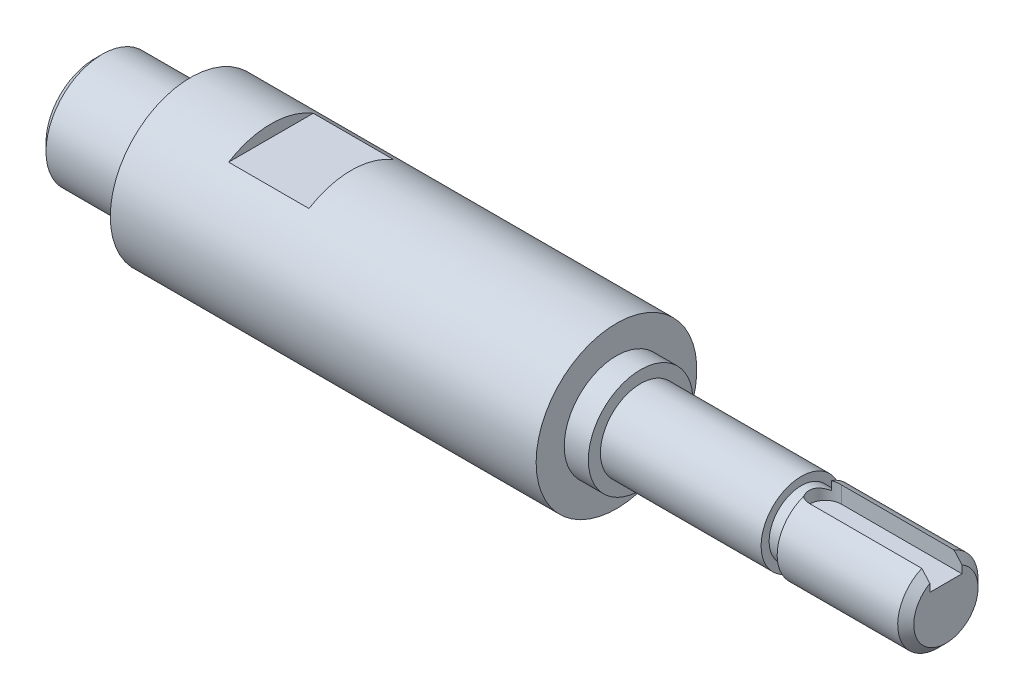
SolidWorks part; units mm, degrees
ref_plane "前视基准面" through (0, 0, 0) normal (0, 0, 1) x (1, 0, 0)
ref_plane "上视基准面" through (0, 0, 0) normal (0, 1, 0) x (1, 0, 0)
ref_plane "右视基准面" through (0, 0, 0) normal (1, 0, 0) x (0, 0, -1)
sketch "草图1" plane through (0, 0, 0) normal (0, 0, 1) x (1, 0, 0)
  line L0 (-49.0671, 0) -> (89.743, 0) construction
  line L1 (-42.5248, 0) -> (-42.5248, 7)
  line L2 (-42.5248, 7) -> (-32.5248, 7)
  line L3 (-32.5248, 7) -> (-32.5248, 6)
  line L4 (-32.5248, 6) -> (-30.5248, 6)
  line L5 (-30.5248, 6) -> (-30.5248, 10)
  line L6 (-30.5248, 10) -> (22.4752, 10)
  line L7 (22.4752, 10) -> (22.4752, 6.5)
  line L8 (47.4752, 5) -> (63.4752, 5)
  line L9 (63.4752, 5) -> (63.4752, 0)
  line L10 (25.4752, 5) -> (45.4752, 5)
  line L11 (45.4752, 5) -> (45.4752, 4)
  line L12 (45.4752, 4) -> (47.4752, 4)
  line L13 (47.4752, 4) -> (47.4752, 5)
  line L14 (-42.5248, 0) -> (63.4752, 0)
  line L16 (22.4752, 6.5) -> (25.4752, 6.5)
  line L17 (25.4752, 6.5) -> (25.4752, 5)
  dimension "D1" = 10
  dimension "D2" = 7
  dimension "D3" = 6
  dimension "D4" = 12
  dimension "D5" = 3
  dimension "D6" = 10
  dimension "D7" = 53
  dimension "D8" = 6.5
  dimension "D9" = 5
  dimension "D10" = 20
  dimension "D11" = 2
  dimension "D12" = 4
  dimension "D13" = 5
  dimension "D14" = 5
  dimension "D15" = 106
  dimension "D16" = 10
revolve "旋转1" add sketch "草图1" angle 360 about L0
chamfer "倒角1" distance 1 angle 45 2 edges at (63.4752, 0, 5) (-42.5248, 0, 7)
sketch "草图2" plane through (0, 0, 0) normal (0, 0, 1) x (1, 0, 0)
  line L0 (-30.5248, 0) -> (22.4752, 0) construction
  line L1 (-30.5248, 6) -> (-30.5248, -6) construction
  line L2 (22.4752, -6.5) -> (22.4752, 6.5) construction
  line L3 (-20.5248, 8.5) -> (-10.5248, 8.5)
  line L4 (-20.5248, -8.5) -> (-10.5248, -8.5)
  line L5 (-20.5248, 8.5) -> (-20.5248, 11.9734)
  line L6 (-20.5248, 11.9734) -> (-10.5248, 11.9734)
  line L7 (-10.5248, 11.9734) -> (-10.5248, 8.5)
  line L8 (-20.5248, -8.5) -> (-20.5248, -11.7285)
  line L9 (-20.5248, -11.7285) -> (-10.5248, -11.7285)
  line L10 (-10.5248, -11.7285) -> (-10.5248, -8.5)
  line L11 (-30.5248, 10) -> (-30.5248, -10) construction
  dimension "D1" = 8.5
  dimension "D2" = 10
  dimension "D3" = 10
extrude "拉伸1" cut sketch "草图2" against normal mid plane 30
ref_plane "基准面1" through (0, 5, 0) normal (0, 1, 0) x (-1, 0, 0)
sketch "草图3" plane through (0, 5, 0) normal (0, 1, 0) x (-1, 0, 0)
  line L0 (-48.4752, 2) -> (-63.4752, 2)
  line L3 (-48.4752, -2) -> (-63.4752, -2)
  line L4 (-63.4752, -2) -> (-63.4752, 2)
  line L5 (-63.4752, 0) -> (42.5248, 0) construction
  line L6 (-63.4752, 4) -> (-63.4752, -4) construction
  line L7 (42.5248, -6) -> (42.5248, 6) construction
  arc A0 (-48.4752, -2) -> (-48.4752, 2) centre (-48.4752, 0) ccw
  dimension "D1" = 4
  dimension "D2" = 15
  dimension "D3" = 0
extrude "拉伸2" cut sketch "草图3" against normal blind 2.5
